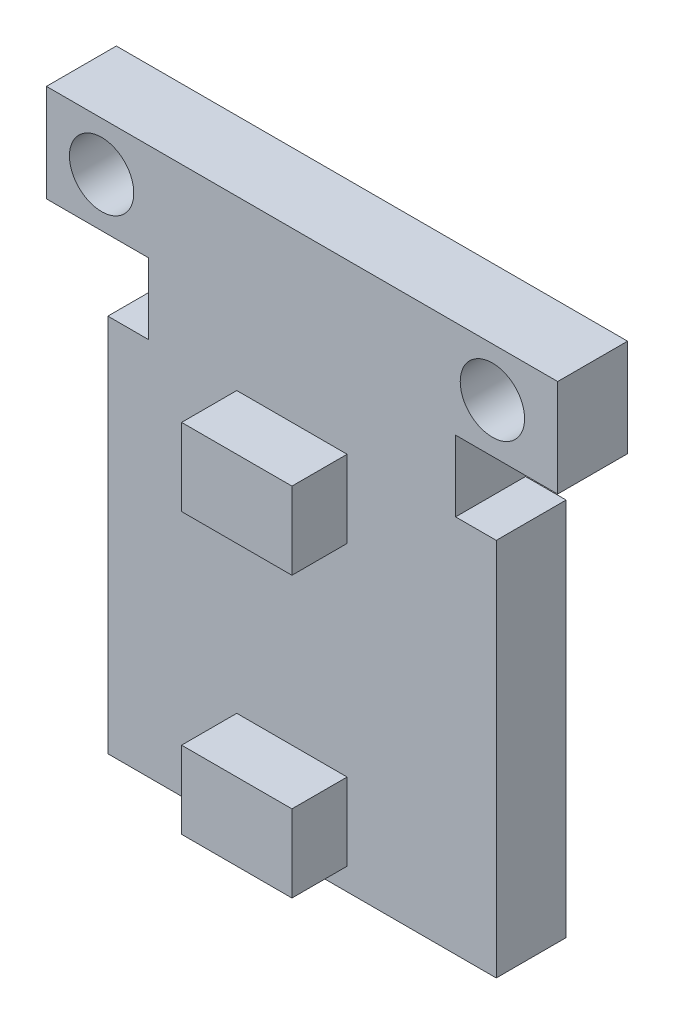
SolidWorks part; units mm, degrees
ref_plane "Front Plane" through (0, 0, 0) normal (0, 0, 1) x (1, 0, 0)
ref_plane "Top Plane" through (0, 0, 0) normal (0, 1, 0) x (1, 0, 0)
ref_plane "Right Plane" through (0, 0, 0) normal (1, 0, 0) x (0, 0, -1)
sketch "Sketch1" plane through (0, 0, 0) normal (0, 0, 1) x (1, 0, 0)
  line L0 (-13.9, 0) -> (13.9, 0)
  line L1 (-13.9, 0) -> (-13.9, -5.3)
  line L2 (13.9, 0) -> (13.9, -5.3)
  line L3 (-13.9, -5.3) -> (-8.35, -5.3)
  line L4 (13.9, -5.3) -> (8.35, -5.3)
  line L5 (-8.35, -5.3) -> (-8.35, -9.15)
  line L6 (8.35, -5.3) -> (8.35, -9.15)
  line L7 (-8.35, -9.15) -> (-10.56, -9.15)
  line L8 (-10.56, -9.15) -> (-10.56, -29.76)
  line L9 (-10.56, -29.76) -> (9.69, -29.76)
  line L11 (10.56, -9.15) -> (8.35, -9.15)
  line L12 (10.56, -9.15) -> (10.56, -29.76)
  line L13 (10.56, -29.76) -> (9.69, -29.76)
  line L14 (-13.9, -2.65) -> (13.9, -2.65) construction
  circle A0 centre (-10.9, -2.65) radius 1.75
  circle A1 centre (10.35, -2.65) radius 1.75
  point P3 (0, 0)
  dimension "D12" = 3.5
  dimension "D1" = 27.8
  dimension "D2" = 5.3
  dimension "D3" = 5.55
  dimension "D4" = 5.55
  dimension "D5" = 3.85
  dimension "D6" = 3.85
  dimension "D7" = 20.61
  dimension "D8" = 20.25
  dimension "D9" = 2.21
  dimension "D10" = 2.21
  dimension "D11" = 3
  dimension "D13" = 21.25
extrude "Boss-Extrude1" add sketch "Sketch1" along normal blind 3.8
sketch "Sketch2" plane through (0, 0, 3.8) normal (0, 0, 1) x (1, 0, 0)
  line L0 (-8.35, -9.15) -> (8.35, -9.15) construction
  line L2 (-3.55, -9.15) -> (2.45, -9.15)
  line L3 (-3.55, -9.15) -> (-3.55, -13.35)
  line L4 (-3.55, -13.35) -> (2.45, -13.35)
  line L5 (2.45, -9.15) -> (2.45, -13.35)
  line L6 (-3.55, -28.55) -> (2.45, -28.55)
  line L7 (-3.55, -28.55) -> (-3.55, -24.35)
  line L8 (-3.55, -24.35) -> (2.45, -24.35)
  line L9 (2.45, -28.55) -> (2.45, -24.35)
  circle A0 centre (-10.9, -2.65) radius 1.75 construction
  dimension "D5" = 7.35
  dimension "D1" = 4.2
  dimension "D2" = 4.2
  dimension "D3" = 6
  dimension "D4" = 6
  dimension "D6" = 11
extrude "Boss-Extrude2" add sketch "Sketch2" along normal blind 3
sketch "Sketch3" plane through (0, 0, 0) normal (0, 0, -1) x (-1, 0, 0)
  text T0 "OLED\r\nSCREEN"
extrude "Cut-Extrude1" cut sketch "Sketch3" against normal blind 1.2
